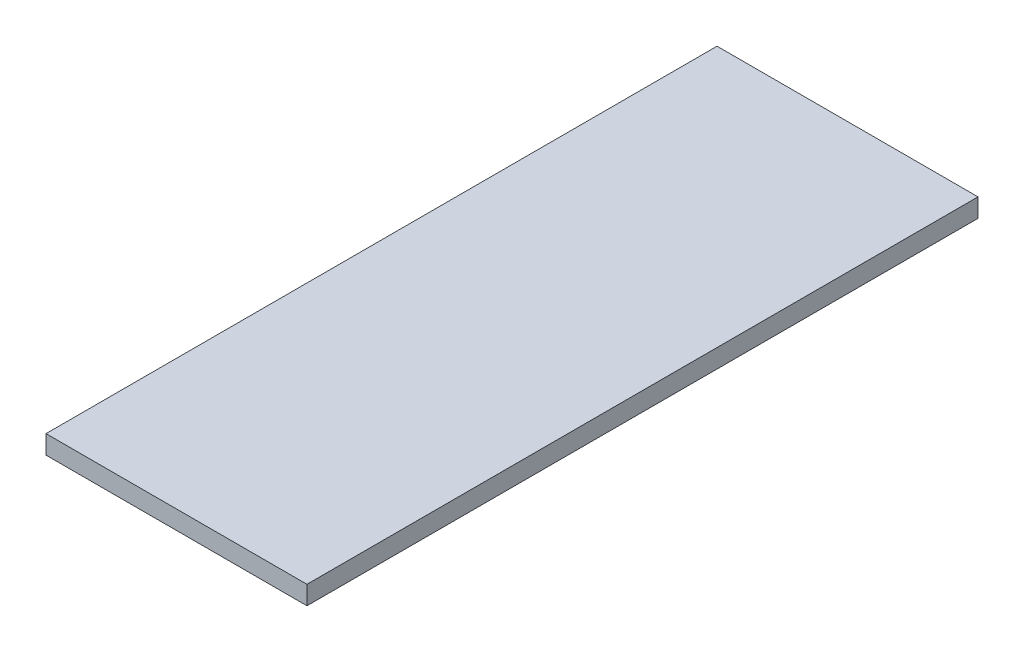
SolidWorks part; units mm, degrees
ref_plane "Front Plane" through (0, 0, 0) normal (0, 0, 1) x (1, 0, 0)
ref_plane "Top Plane" through (0, 0, 0) normal (0, 1, 0) x (1, 0, 0)
ref_plane "Right Plane" through (0, 0, 0) normal (1, 0, 0) x (0, 0, -1)
sketch "Sketch1" plane through (0, 0, 0) normal (0, 1, 0) x (1, 0, 0)
  line L1 (-35, -90) -> (35, -90)
  line L2 (-35, -90) -> (-35, 90)
  line L3 (-35, 90) -> (35, 90)
  line L4 (35, -90) -> (35, 90)
  line L5 (-35, -90) -> (35, 90) construction
  line L6 (-35, 90) -> (35, -90) construction
  point P0 (0, 0)
  dimension "D1" = 70
  dimension "D2" = 180
extrude "Boss-Extrude1" add sketch "Sketch1" along normal blind 5
sketch "Sketch2" plane through (0, 0, 0) normal (0, -1, 0) x (1, 0, 0)
  line L0 (-35, -90) -> (-35, 90) construction
  line L1 (35, -90) -> (-35, -90) construction
  circle A0 centre (-30, 84.5691) radius 4
  circle A1 centre (29.8955, 84.5691) radius 4
  circle A2 centre (-30, -85) radius 4
  circle A3 centre (29.8955, -85) radius 4
  point P8 (29.8955, 84.5691)
  point P11 (-27.868, 46.6604)
  point P12 (29.8955, -36.9498)
  point P13 (29.8955, -85.9352)
  point P16 (-30, -85)
  dimension "D1" = 5
  dimension "D2" = 5
extrude "Cut-Extrude1" cut sketch "Sketch2" against normal blind 2
